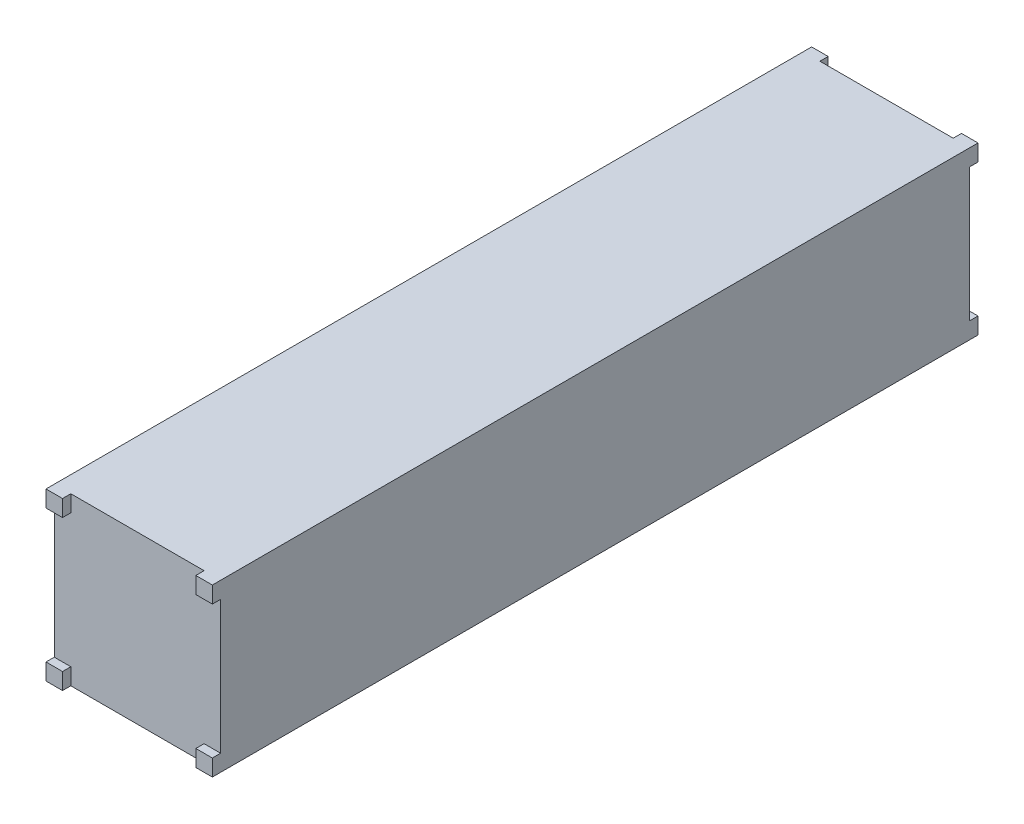
SolidWorks part; units mm, degrees
ref_plane "Front Plane" through (0, 0, 0) normal (0, 0, 1) x (1, 0, 0)
ref_plane "Top Plane" through (0, 0, 0) normal (0, 1, 0) x (1, 0, 0)
ref_plane "Right Plane" through (0, 0, 0) normal (1, 0, 0) x (0, 0, -1)
sketch "Sketch1" plane through (0, 0, 0) normal (0, 0, 1) x (1, 0, 0)
  line L1 (50.3, -50.3) -> (-50.3, -50.3)
  line L2 (50.3, -50.3) -> (50.3, 50.3)
  line L3 (50.3, 50.3) -> (-50.3, 50.3)
  line L4 (-50.3, -50.3) -> (-50.3, 50.3)
  line L5 (50.3, -50.3) -> (-50.3, 50.3) construction
  line L6 (50.3, 50.3) -> (-50.3, -50.3) construction
  point P0 (0, 0)
  dimension "D1" = 100.6
  dimension "D2" = 100.6
extrude "Boss-Extrude1" add sketch "Sketch1" along normal mid plane 453
sketch "Sketch2" plane through (0, 0, 226.5) normal (0, 0, 1) x (1, 0, 0)
  line L0 (0, 50.3) -> (0, -50.3) construction
  line L1 (-50.3, 50.3) -> (-40.3, 50.3)
  line L2 (-50.3, 50.3) -> (-50.3, 40.3)
  line L3 (-50.3, 40.3) -> (-40.3, 40.3)
  line L4 (-40.3, 50.3) -> (-40.3, 40.3)
  line L5 (50.3, 50.3) -> (-50.3, 50.3) construction
  line L6 (-50.3, -50.3) -> (50.3, -50.3) construction
  line L7 (50.3, 40.3) -> (40.3, 40.3)
  line L8 (40.3, 50.3) -> (40.3, 40.3)
  line L9 (50.3, 50.3) -> (40.3, 50.3)
  line L10 (50.3, 50.3) -> (50.3, 40.3)
  line L11 (-50.3, 0) -> (50.3, 0) construction
  line L12 (-50.3, 50.3) -> (-50.3, -50.3) construction
  line L13 (50.3, -50.3) -> (50.3, 50.3) construction
  line L14 (50.3, -50.3) -> (50.3, -40.3)
  line L15 (50.3, -50.3) -> (40.3, -50.3)
  line L16 (40.3, -50.3) -> (40.3, -40.3)
  line L17 (50.3, -40.3) -> (40.3, -40.3)
  line L18 (-50.3, -40.3) -> (-40.3, -40.3)
  line L19 (-40.3, -50.3) -> (-40.3, -40.3)
  line L20 (-50.3, -50.3) -> (-40.3, -50.3)
  line L21 (-50.3, -50.3) -> (-50.3, -40.3)
  dimension "D1" = 10
  dimension "D2" = 10
extrude "Boss-Extrude2" add sketch "Sketch2" along normal blind 5
sketch "Sketch3" plane through (0, 0, -226.5) normal (0, 0, -1) x (-1, 0, 0)
  line L0 (0, 50.3) -> (0, 0) construction
  line L1 (-50.3, 50.3) -> (-40.3, 50.3)
  line L2 (-50.3, 50.3) -> (-50.3, 40.3)
  line L3 (-50.3, 40.3) -> (-40.3, 40.3)
  line L4 (-40.3, 50.3) -> (-40.3, 40.3)
  line L5 (-50.3, 50.3) -> (50.3, 50.3) construction
  line L6 (0, 0) -> (50.3, 0) construction
  line L7 (50.3, 50.3) -> (50.3, -50.3) construction
  line L8 (50.3, 40.3) -> (40.3, 40.3)
  line L9 (40.3, 50.3) -> (40.3, 40.3)
  line L10 (50.3, 50.3) -> (40.3, 50.3)
  line L11 (50.3, 50.3) -> (50.3, 40.3)
  line L12 (50.3, -50.3) -> (50.3, -40.3)
  line L13 (50.3, -50.3) -> (40.3, -50.3)
  line L14 (40.3, -50.3) -> (40.3, -40.3)
  line L15 (50.3, -40.3) -> (40.3, -40.3)
  line L16 (-50.3, -40.3) -> (-40.3, -40.3)
  line L17 (-40.3, -50.3) -> (-40.3, -40.3)
  line L18 (-50.3, -50.3) -> (-40.3, -50.3)
  line L19 (-50.3, -50.3) -> (-50.3, -40.3)
  dimension "D1" = 10
  dimension "D2" = 10
extrude "Boss-Extrude3" add sketch "Sketch3" along normal blind 5
